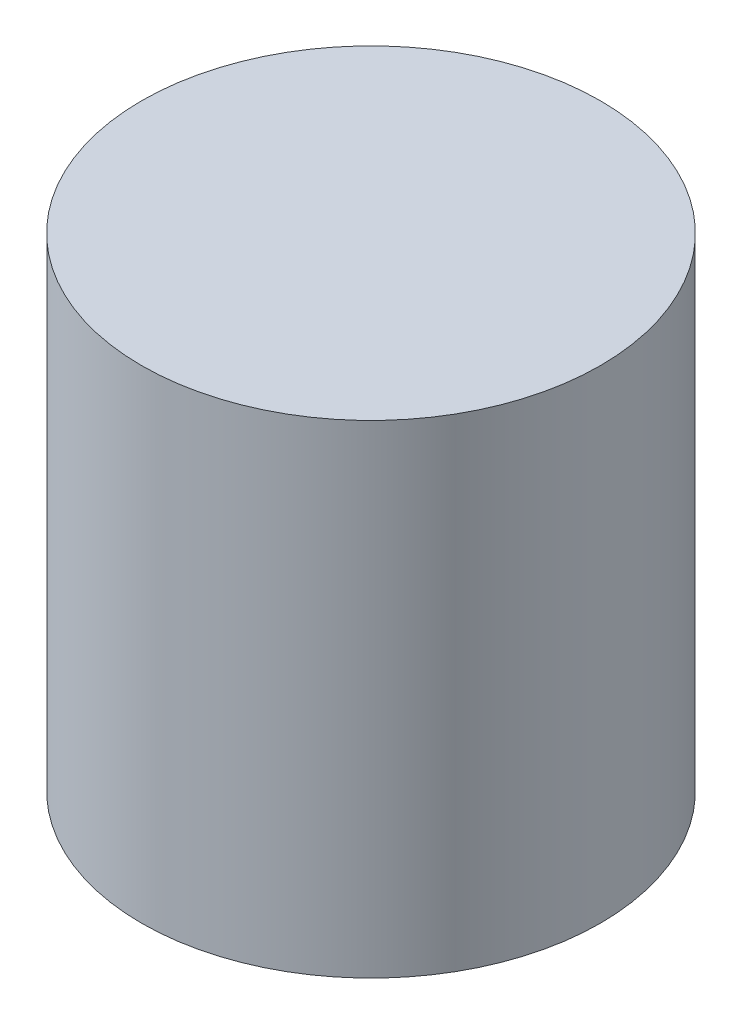
SolidWorks part; units mm, degrees
ref_plane "Front Plane" through (0, 0, 0) normal (0, 0, 1) x (1, 0, 0)
ref_plane "Top Plane" through (0, 0, 0) normal (0, 1, 0) x (1, 0, 0)
ref_plane "Right Plane" through (0, 0, 0) normal (1, 0, 0) x (0, 0, -1)
sketch "Sketch1" plane through (0, 0, 0) normal (0, 1, 0) x (1, 0, 0)
  circle A0 centre (0, 0) radius 30.1625
  dimension "D1" = 60.325
extrude "Boss-Extrude1" add sketch "Sketch1" along normal blind 63.5
